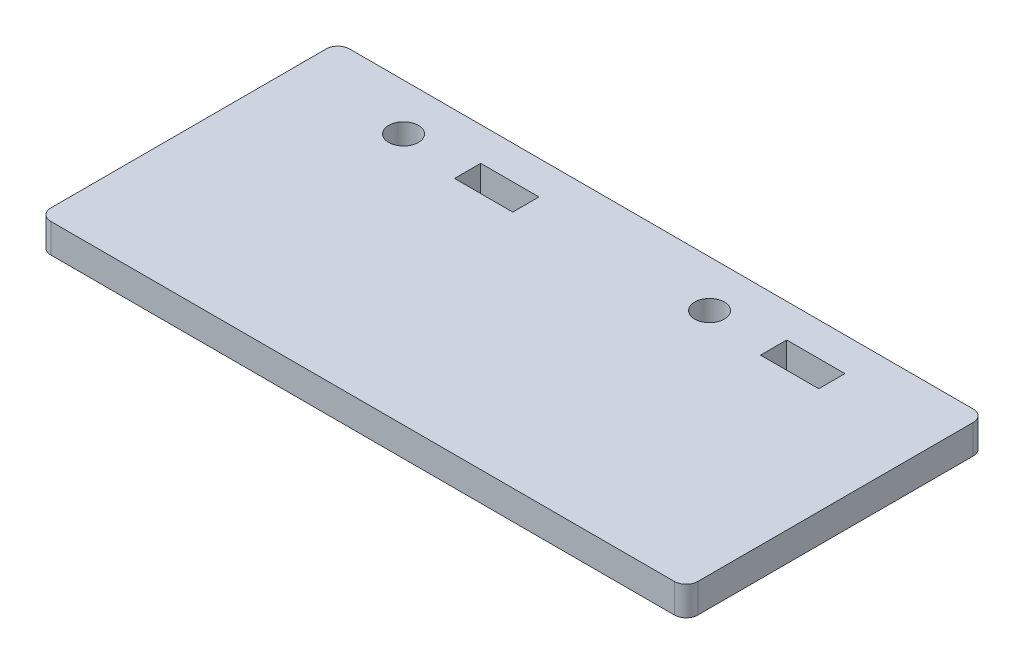
SolidWorks part; units mm, degrees
ref_plane "Front Plane" through (0, 0, 0) normal (0, 0, 1) x (1, 0, 0)
ref_plane "Top Plane" through (0, 0, 0) normal (0, 1, 0) x (1, 0, 0)
ref_plane "Right Plane" through (0, 0, 0) normal (1, 0, 0) x (0, 0, -1)
sketch "Sketch1" plane through (0, 0, 0) normal (0, 1, 0) x (1, 0, 0)
  line L1 (55.55, -25.65) -> (-55.55, -25.65)
  line L2 (55.55, -25.65) -> (55.55, 25.65)
  line L3 (55.55, 25.65) -> (-55.55, 25.65)
  line L4 (-55.55, -25.65) -> (-55.55, 25.65)
  line L5 (55.55, -25.65) -> (-55.55, 25.65) construction
  line L6 (55.55, 25.65) -> (-55.55, -25.65) construction
  point P0 (0, 0)
  dimension "D1" = 111.1
  dimension "D2" = 51.3
extrude "Boss-Extrude1" add sketch "Sketch1" along normal blind 5
sketch "Sketch9" plane through (0, 0, 0) normal (0, -1, 0) x (1, 0, 0)
  line L0 (-55.55, -25.65) -> (-55.55, 25.65) construction
  line L1 (-50.55, -18.65) -> (-45.55, -18.65)
  line L2 (-50.55, -18.65) -> (-50.55, -22.65)
  line L3 (-50.55, -22.65) -> (-45.55, -22.65)
  line L4 (-45.55, -18.65) -> (-45.55, -22.65)
  line L5 (-50.55, -18.65) -> (-45.55, -22.65) construction
  line L6 (-50.55, -22.65) -> (-45.55, -18.65) construction
  line L7 (55.55, -25.65) -> (-55.55, -25.65) construction
  line L8 (0, -25.65) -> (0, 25.65) construction
  line L9 (-55.55, 25.65) -> (55.55, 25.65) construction
  line L10 (50.55, -18.65) -> (50.55, -22.65)
  line L11 (50.55, -22.65) -> (45.55, -22.65)
  line L12 (45.55, -18.65) -> (45.55, -22.65)
  line L13 (50.55, -18.65) -> (45.55, -18.65)
  point P0 (-48.05, -20.65)
  dimension "D1" = 4
  dimension "D2" = 5
  dimension "D3" = 5
  dimension "D4" = 3
extrude "Boss-Extrude5" add sketch "Sketch9" along normal blind 3
sketch "Sketch10" plane through (0, 5, 0) normal (0, 1, 0) x (1, 0, 0)
  line L0 (-55.55, 17.65) -> (55.55, 17.65) construction
  line L1 (-55.55, 25.65) -> (-55.55, -25.65) construction
  line L2 (55.55, -25.65) -> (55.55, 25.65) construction
  line L3 (0, 17.65) -> (0, -25.65) construction
  line L5 (-55.55, -25.65) -> (55.55, -25.65) construction
  line L7 (-52.55, 0) -> (0, 0) construction
  line L9 (-15.275, 15.4) -> (-25.275, 15.4)
  line L10 (-15.275, 15.4) -> (-15.275, 19.9)
  line L11 (-15.275, 19.9) -> (-25.275, 19.9)
  line L12 (-25.275, 15.4) -> (-25.275, 19.9)
  line L13 (-15.275, 15.4) -> (-25.275, 19.9) construction
  line L14 (-15.275, 19.9) -> (-25.275, 15.4) construction
  line L15 (52.55, -22.65) -> (-52.55, -22.65) construction
  line L16 (52.55, -22.65) -> (52.55, 22.65) construction
  line L18 (-52.55, -22.65) -> (-52.55, 22.65) construction
  line L22 (0, 22.65) -> (52.55, 22.65) construction
  line L27 (-52.55, 22.65) -> (0, 22.65) construction
  line L28 (-26.275, 0) -> (-26.275, 17.65) construction
  line L33 (37.275, 15.4) -> (27.275, 15.4)
  line L34 (37.275, 15.4) -> (37.275, 19.9)
  line L35 (26.275, 0) -> (26.275, 17.65) construction
  line L36 (37.275, 19.9) -> (27.275, 19.9)
  line L37 (27.275, 15.4) -> (27.275, 19.9)
  line L38 (37.275, 15.4) -> (27.275, 19.9) construction
  line L39 (37.275, 19.9) -> (27.275, 15.4) construction
  circle A0 centre (-36.275, 17.65) radius 2.55
  circle A3 centre (16.275, 17.65) radius 2.55
  point P18 (-20.275, 17.65)
  point P23 (0, 0)
  point P29 (32.275, 17.65)
  dimension "D1" = 5.1
  dimension "D11" = 6
  dimension "D8" = 10
  dimension "D2" = 10
  dimension "D3" = 4.5
  dimension "D4" = 5
  dimension "D5" = 3
  dimension "D6" = 3
  dimension "D7" = 3
  dimension "D9" = 6
  dimension "D10" = 10
extrude "Cut-Extrude1" cut sketch "Sketch10" against normal blind 10
sketch "Sketch11" plane through (0, 0, 0) normal (0, -1, 0) x (1, 0, 0)
  line L0 (-20.275, -15.4) -> (-20.275, -19.9) construction
  line L1 (-25.275, -15.4) -> (-15.275, -15.4) construction
  line L2 (-15.275, -19.9) -> (-25.275, -19.9) construction
  line L3 (32.275, -15.4) -> (32.275, -19.9) construction
  line L4 (27.275, -15.4) -> (37.275, -15.4) construction
  line L5 (37.275, -19.9) -> (27.275, -19.9) construction
  line L6 (-30.025, -17.65) -> (-10.525, -17.65) construction
  line L7 (22.525, -17.65) -> (42.025, -17.65) construction
  circle A0 centre (-30.025, -17.65) radius 1.8
  circle A1 centre (-10.525, -17.65) radius 1.8
  circle A2 centre (22.525, -17.65) radius 1.8
  circle A3 centre (42.025, -17.65) radius 1.8
  point P18 (-20.275, -17.65)
  point P19 (-20.275, -17.65)
  point P22 (32.275, -17.65)
  dimension "D1" = 3.6
  dimension "D2" = 19.5
extrude "Cut-Extrude2" cut sketch "Sketch11" against normal blind 3
fillet "Fillet1" radius 2 4 edges at (-55.55, 2.5, -25.65) (-55.55, 2.5, 25.65) (55.55, 2.5, 25.65) (55.55, 2.5, -25.65)
